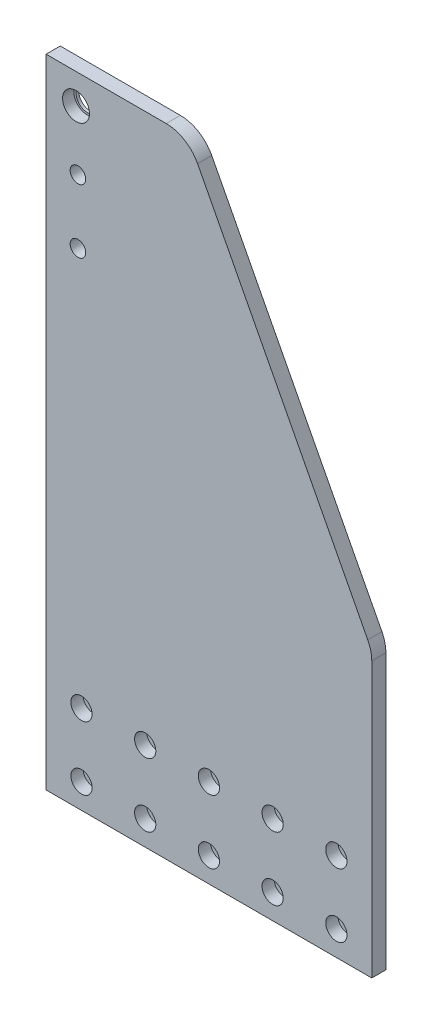
SolidWorks part; units mm, degrees
material "1.0037 (S235JR)"
ref_plane "Ön Düzlem" through (0, 0, 0) normal (0, 0, 1) x (1, 0, 0)
ref_plane "Üst Düzlem" through (0, 0, 0) normal (0, 1, 0) x (1, 0, 0)
ref_plane "Sağ Düzlem" through (0, 0, 0) normal (1, 0, 0) x (0, 0, -1)
sketch "Sketch1" plane through (0, 0, 0) normal (0, 0, 1) x (1, 0, 0)
  line L8 (-115, 450) -> (-115, 0)
  line L10 (-115, 0) -> (115, 0)
  line L14 (115, 200) -> (115, 0)
  line L21 (115, 200) -> (-15, 450)
  line L22 (-15, 450) -> (-115, 450)
  dimension "D1" = 230
  dimension "D2" = 100
  dimension "D3" = 450
  dimension "D6" = 200
extrude "Boss-Extrude1" add sketch "Sketch1" along normal mid plane 10
hole_wizard "CBORE for M8 Hex Socket Head Cap Screw1" positions "Sketch2" profile "Sketch3" counterbore size "M8" standard "ISO" end condition through all
sketch "Sketch2" plane through (0, 0, 5) normal (0, 0, 1) x (1, 0, 0)
  line L0 (-115, 450) -> (-115, 0) construction
  line L2 (115, 0) -> (115, 200) construction
  point P2 (-90, 17.5)
  point P4 (-45, 17.5)
  point P6 (45, 17.5)
  point P8 (90, 17.5)
  point P10 (0, 17.5)
  point P34 (-90, 62.5)
  point P35 (-45, 62.5)
  point P36 (45, 62.5)
  point P37 (90, 62.5)
  point P38 (0, 62.5)
  dimension "D1" = 17.5
  dimension "D2" = 25
  dimension "D3" = 25
  dimension "D4" = 45
  dimension "D5" = 45
  dimension "D6" = 45
  dimension "D7" = 2
sketch "Sketch3" plane through (-90, 17.5, 5) normal (1, 0, 0) x (0, -1, 0)
  line L0 (0, 0) -> (0, 10)
  line L1 (0, 10) -> (4.5, 10)
  line L3 (4.5, 10) -> (4.5, 8.6)
  line L4 (4.5, 8.6) -> (7.5, 8.6)
  line L5 (7.5, 8.6) -> (7.5, 0)
  line L7 (7.5, 0) -> (0, 0)
  line L11 (0, -6.35) -> (0, 107.95) construction
  dimension "Thru Hole Dia." = 9
  dimension "Thru Hole Depth" = 10
  dimension "C'Bore Dia." = 15
  dimension "C'Bore Depth" = 8.6
sketch "Sketch4" plane through (-115, 0, 0) normal (-1, 0, 0) x (0, 0, 1)
  line L0 (-5, 450) -> (-5, 0) construction
  line L1 (-5, 125) -> (-1.5, 125)
  line L2 (-5, 125) -> (-5, 95)
  line L3 (-5, 95) -> (-1.5, 95)
  line L4 (-1.5, 125) -> (-1.5, 95)
  line L5 (5, 0) -> (-5, 0) construction
  dimension "D1" = 30
  dimension "D2" = 95
  dimension "D3" = 3.5
extrude "Cut-Extrude1" [suppressed] cut sketch "Sketch4" against normal through all
sketch "Sketch5" plane through (0, 0, 5) normal (0, 0, 1) x (1, 0, 0)
  line L0 (-115, 450) -> (-115, 0) construction
  line L1 (-15, 450) -> (-115, 450) construction
  circle A0 centre (-93.85, 428.85) radius 9.5
  dimension "D3" = 19
  dimension "D1" = 21.15
  dimension "D2" = 21.15
extrude "Cut-Extrude2" cut sketch "Sketch5" against normal blind 8
sketch "Sketch6" plane through (0, 0, -3) normal (0, 0, 1) x (1, 0, 0)
  circle A0 centre (-93.85, 428.85) radius 8
  dimension "18" = 16
extrude "Cut-Extrude3" cut sketch "Sketch6" against normal through all
sketch "Sketch7" plane through (0, 0, 5) normal (0, 0, 1) x (1, 0, 0)
  line L0 (-15, 450) -> (-115, 450) construction
  line L1 (-115, 450) -> (-115, 0) construction
  circle A0 centre (-92.5, 387.5) radius 4.5
  circle A1 centre (-92.5, 342.5) radius 4.5
  dimension "D1" = 62.5
  dimension "D4" = 9
  dimension "D2" = 45
  dimension "D3" = 22.5
fillet "Fillet1" radius 25 2 edges at (115, 200, 0) (-15, 450, 0)
hole_wizard "M10 Clearance Hole1" positions "Sketch8" profile "Sketch9" hole size "M10" standard "ISO"
sketch "Sketch8" plane through (0, 0, 5) normal (0, 0, 1) x (1, 0, 0)
  point P0 (-92.5, 387.5)
  point P3 (-92.5, 342.5)
sketch "Sketch9" plane through (-92.5, 387.5, 5) normal (1, 0, 0) x (0, -1, 0)
  line L0 (0, 0) -> (0, 28.3047)
  line L1 (0, 28.3047) -> (5.5, 25)
  line L2 (5.5, 25) -> (5.5, 0)
  line L5 (5.5, 0) -> (0, 0)
  line L10 (0, 28.3047) -> (-5.5, 25) construction
  line L11 (0, -6.35) -> (0, 107.95) construction
  dimension "Hole Dia." = 11
  dimension "Hole Depth" = 25
  dimension "Drill Angle" = 118
